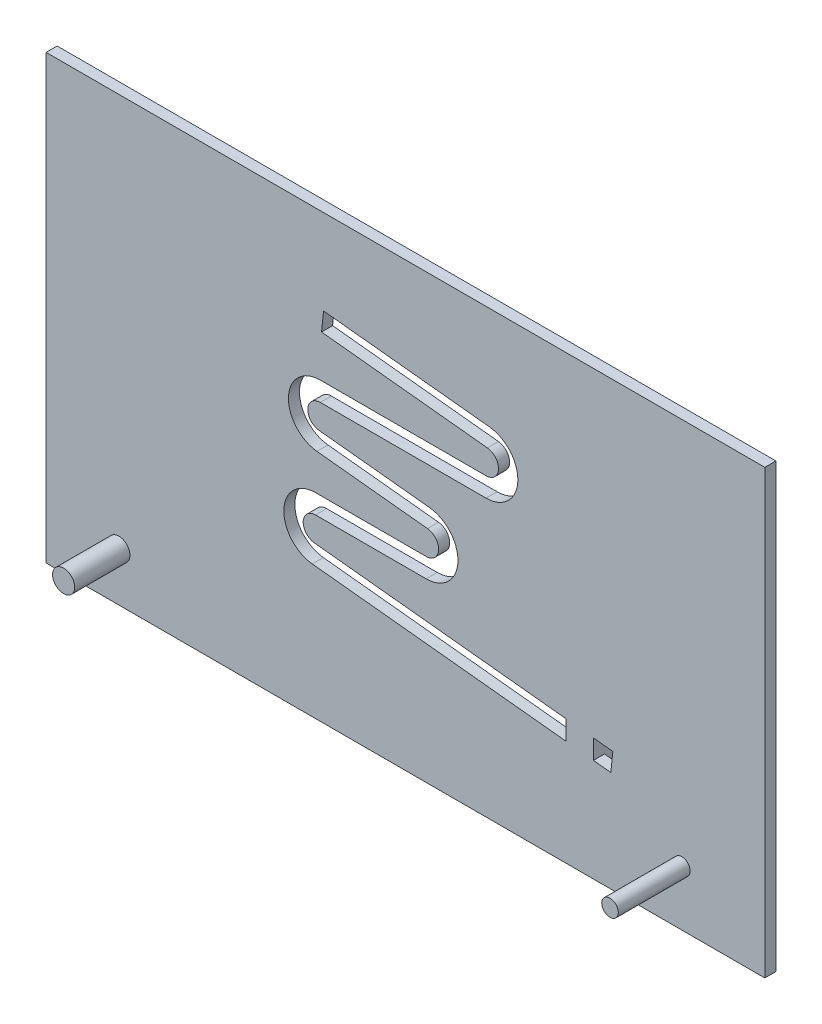
SolidWorks part; units mm, degrees
material "ABS"
ref_plane "Front Plane" through (0, 0, 0) normal (0, 0, 1) x (1, 0, 0)
ref_plane "Top Plane" through (0, 0, 0) normal (0, 1, 0) x (1, 0, 0)
ref_plane "Right Plane" through (0, 0, 0) normal (1, 0, 0) x (0, 0, -1)
sketch "Sketch1" plane through (0, 0, 0) normal (0, 0, 1) x (1, 0, 0)
  line L1 (0, 0) -> (130, 0)
  line L2 (0, 0) -> (0, 80)
  line L3 (0, 80) -> (130, 80)
  line L4 (130, 0) -> (130, 80)
  dimension "D1" = 80
  dimension "D2" = 130
extrude "Boss-Extrude1" add sketch "Sketch1" along normal blind 2
sketch "Sketch2" plane through (0, 0, 2) normal (0, 0, 1) x (1, 0, 0)
  line L1 (49.1638, 43.7339) -> (69.1638, 41.6318)
  line L2 (68.7457, 33.6537) -> (48.7457, 33.6537)
  line L3 (48.3275, 25.6756) -> (102.3275, 20)
  line L5 (49.5819, 51.712) -> (79.5819, 51.712)
  line L7 (130, 80) -> (0, 80) construction
  line L9 (0, 80) -> (0, 0) construction
  line L12 (80, 59.6901) -> (50, 62.8432)
  line L14 (102.3275, 20) -> (27.6458, 20) construction
  arc A0 (49.1638, 43.7339) -> (49.5819, 51.712) centre (49.5819, 47.712) cw
  arc A1 (48.3275, 25.6756) -> (48.7457, 33.6537) centre (48.7457, 29.6537) cw
  arc A2 (68.7457, 33.6537) -> (69.1638, 41.6318) centre (68.7457, 37.6537) ccw
  arc A4 (79.5819, 51.712) -> (80, 59.6901) centre (79.5819, 55.712) ccw
  point P20 (65, 80)
  point P21 (0, 40)
  point P24 (50, 62.8432)
  dimension "D3" = 4
  dimension "D5" = 4
  dimension "D6" = 4
  dimension "D7" = 20
  dimension "D8" = 4
  dimension "D1" = 6
  dimension "D2" = 20
  dimension "D4" = 6
  dimension "D9" = 54
  dimension "15" = 20
  dimension "D10" = 50
  dimension "D11" = 30
  dimension "D12" = 30
extrude "Cut-Extrude-Thin1" cut sketch "Sketch2" against normal blind 3.2 thin thin type mid plane wall 3.5
sketch "Sketch5" plane through (0, 0, 0) normal (0, 0, -1) x (-1, 0, 0)
  line L0 (-130, 0) -> (-130, 80) construction
  line L1 (0, 0) -> (-130, 0) construction
  circle A0 centre (-115, 10) radius 1.5
  dimension "D1" = 3
  dimension "D3" = 10
  dimension "D2" = 15
extrude "Boss-Extrude2" add sketch "Sketch5" along normal blind 10 and the other way blind 15
sketch "Sketch6" plane through (0, 0, 0) normal (0, 0, -1) x (-1, 0, 0)
  circle A0 centre (-13.1626, 8.7939) radius 2
  dimension "D1" = 4
extrude "Boss-Extrude3" add sketch "Sketch6" along normal blind 10 and the other way blind 12
sketch "Sketch4" plane through (0, 0, 2) normal (0, 0, 1) x (1, 0, 0)
sketch "Sketch7" plane through (0, 0, 2) normal (0, 0, 1) x (1, 0, 0)
  line L0 (49.1638, 43.7339) -> (69.1638, 41.6318) construction
  line L1 (80, 59.6901) -> (50, 62.8432) construction
  line L2 (49.5819, 51.712) -> (79.5819, 51.712) construction
  line L3 (68.7457, 33.6537) -> (48.7457, 33.6537) construction
  line L12 (48.3275, 25.6756) -> (102.3275, 20) construction
  line L13 (49.1638, 43.7339) -> (69.1638, 41.6318)
  line L14 (80, 59.6901) -> (50, 62.8432)
  line L15 (49.5819, 51.712) -> (79.5819, 51.712)
  line L16 (68.7457, 33.6537) -> (48.7457, 33.6537)
  line L17 (48.3275, 25.6756) -> (102.3275, 20)
  line L18 (80, 59.6901) -> (79.5819, 55.712) construction
  line L19 (79.5819, 55.712) -> (79.5819, 51.712) construction
  line L20 (49.5819, 51.712) -> (49.5819, 47.712)
  line L21 (49.5819, 47.712) -> (49.1638, 43.7339)
  arc A0 (79.5819, 51.712) -> (80, 59.6901) centre (79.5819, 55.712) ccw construction
  arc A1 (49.5819, 51.712) -> (49.1638, 43.7339) centre (49.5819, 47.712) ccw construction
  arc A2 (68.7457, 33.6537) -> (69.1638, 41.6318) centre (68.7457, 37.6537) ccw construction
  arc A3 (48.7457, 33.6537) -> (48.3275, 25.6756) centre (48.7457, 29.6537) ccw construction
  arc A4 (79.5819, 51.712) -> (80, 59.6901) centre (79.5819, 55.712) ccw
  arc A5 (49.5819, 51.712) -> (49.1638, 43.7339) centre (49.5819, 47.712) ccw
  arc A6 (68.7457, 33.6537) -> (69.1638, 41.6318) centre (68.7457, 37.6537) ccw
  arc A7 (48.7457, 33.6537) -> (48.3275, 25.6756) centre (48.7457, 29.6537) ccw
  point P15 (50, 62.8432)
  point P25 (80, 59.6901)
  point P103 (94.3367, 61.4434)
  point P108 (100.8842, 60.3345)
sketch "Sketch9" plane through (0, 0, 2) normal (0, 0, 1) x (1, 0, 0)
  line L0 (130, 0) -> (130, 80) construction
  line L1 (99, 65) -> (94, 65)
  line L2 (99, 65) -> (99, 15)
  line L3 (99, 15) -> (94, 15)
  line L4 (94, 65) -> (94, 15)
  line L5 (0, 0) -> (130, 0) construction
  dimension "D1" = 5
  dimension "D2" = 31
  dimension "D3" = 50
  dimension "D4" = 15
extrude "Boss-Extrude5" add sketch "Sketch9" against normal blind 10.5 contours L4 L3 L2 L1
sketch "Sketch11" plane through (94, 0, 0) normal (-1, 0, 0) x (0, 0, 1)
  line L0 (0, 55.712) -> (-8.5, 55.712) construction
  line L2 (-8.5, 65) -> (-8.5, 15) construction
  line L3 (0, 55.712) -> (2, 55.712) construction
  line L4 (0, 37.6537) -> (-8.5, 37.6537) construction
  line L6 (0, 22.8378) -> (-8.5, 22.8378) construction
  line L8 (0, 80) -> (0, 0) construction
  line L9 (0, 37.6537) -> (2, 37.6537) construction
  line L10 (0, 15) -> (0, 19.1156) construction
  line L11 (2, 25.6756) -> (2, 20) construction
  line L12 (2, 22.8378) -> (0, 22.8378) construction
  circle A0 centre (-4.25, 55.712) radius 1.5
  circle A1 centre (-4.25, 37.6537) radius 1.5
  circle A2 centre (-4.25, 22.8378) radius 1.5
  dimension "D1" = 3
  dimension "D2" = 3
  dimension "D3" = 3
extrude "Cut-Extrude1" cut sketch "Sketch11" against normal blind 7.5
